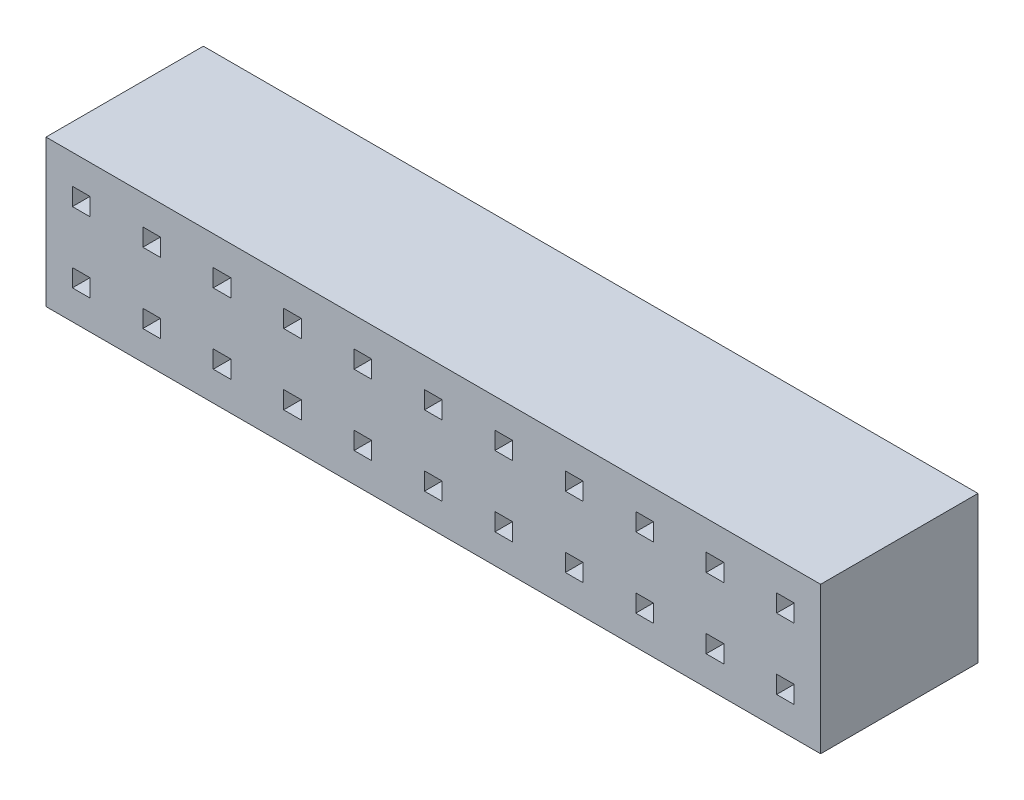
SolidWorks part; units mm, degrees
ref_plane "Front Plane" through (0, 0, 0) normal (0, 0, 1) x (1, 0, 0)
ref_plane "Top Plane" through (0, 0, 0) normal (0, 1, 0) x (1, 0, 0)
ref_plane "Right Plane" through (0, 0, 0) normal (1, 0, 0) x (0, 0, -1)
sketch "Sketch1" plane through (0, 0, 0) normal (0, 0, 1) x (1, 0, 0)
  line L1 (0, -0.085) -> (22, -0.085)
  line L2 (0, -0.085) -> (0, 4.085)
  line L3 (0, 4.085) -> (22, 4.085)
  line L4 (22, -0.085) -> (22, 4.085)
extrude "Boss-Extrude1" add sketch "Sketch1" along normal blind 4.47
sketch "Sketch2" plane through (0, 0, 4.47) normal (0, 0, 1) x (1, 0, 0)
  line L1 (0.75, 0.75) -> (1.25, 0.75)
  line L2 (0.75, 0.75) -> (0.75, 1.25)
  line L3 (0.75, 1.25) -> (1.25, 1.25)
  line L4 (1.25, 0.75) -> (1.25, 1.25)
  line L88 (2.75, 0.75) -> (3.25, 0.75)
  line L89 (2.75, 0.75) -> (2.75, 1.25)
  line L90 (2.75, 1.25) -> (3.25, 1.25)
  line L91 (3.25, 0.75) -> (3.25, 1.25)
  line L92 (4.75, 0.75) -> (5.25, 0.75)
  line L93 (4.75, 0.75) -> (4.75, 1.25)
  line L94 (4.75, 1.25) -> (5.25, 1.25)
  line L95 (5.25, 0.75) -> (5.25, 1.25)
  line L96 (6.75, 0.75) -> (7.25, 0.75)
  line L97 (6.75, 0.75) -> (6.75, 1.25)
  line L98 (6.75, 1.25) -> (7.25, 1.25)
  line L99 (7.25, 0.75) -> (7.25, 1.25)
  line L100 (8.75, 0.75) -> (9.25, 0.75)
  line L101 (8.75, 0.75) -> (8.75, 1.25)
  line L102 (8.75, 1.25) -> (9.25, 1.25)
  line L103 (9.25, 0.75) -> (9.25, 1.25)
  line L104 (10.75, 0.75) -> (11.25, 0.75)
  line L105 (10.75, 0.75) -> (10.75, 1.25)
  line L106 (10.75, 1.25) -> (11.25, 1.25)
  line L107 (11.25, 0.75) -> (11.25, 1.25)
  line L108 (12.75, 0.75) -> (13.25, 0.75)
  line L109 (12.75, 0.75) -> (12.75, 1.25)
  line L110 (12.75, 1.25) -> (13.25, 1.25)
  line L111 (13.25, 0.75) -> (13.25, 1.25)
  line L112 (14.75, 0.75) -> (15.25, 0.75)
  line L113 (14.75, 0.75) -> (14.75, 1.25)
  line L114 (14.75, 1.25) -> (15.25, 1.25)
  line L115 (15.25, 0.75) -> (15.25, 1.25)
  line L116 (16.75, 0.75) -> (17.25, 0.75)
  line L117 (16.75, 0.75) -> (16.75, 1.25)
  line L118 (16.75, 1.25) -> (17.25, 1.25)
  line L119 (17.25, 0.75) -> (17.25, 1.25)
  line L120 (18.75, 0.75) -> (19.25, 0.75)
  line L121 (18.75, 0.75) -> (18.75, 1.25)
  line L122 (18.75, 1.25) -> (19.25, 1.25)
  line L123 (19.25, 0.75) -> (19.25, 1.25)
  line L124 (20.75, 0.75) -> (21.25, 0.75)
  line L125 (20.75, 0.75) -> (20.75, 1.25)
  line L126 (20.75, 1.25) -> (21.25, 1.25)
  line L127 (21.25, 0.75) -> (21.25, 1.25)
  line L128 (0.75, 2.75) -> (1.25, 2.75)
  line L129 (0.75, 2.75) -> (0.75, 3.25)
  line L130 (0.75, 3.25) -> (1.25, 3.25)
  line L131 (1.25, 2.75) -> (1.25, 3.25)
  line L132 (2.75, 2.75) -> (3.25, 2.75)
  line L133 (2.75, 2.75) -> (2.75, 3.25)
  line L134 (2.75, 3.25) -> (3.25, 3.25)
  line L135 (3.25, 2.75) -> (3.25, 3.25)
  line L136 (4.75, 2.75) -> (5.25, 2.75)
  line L137 (4.75, 2.75) -> (4.75, 3.25)
  line L138 (4.75, 3.25) -> (5.25, 3.25)
  line L139 (5.25, 2.75) -> (5.25, 3.25)
  line L140 (6.75, 2.75) -> (7.25, 2.75)
  line L141 (6.75, 2.75) -> (6.75, 3.25)
  line L142 (6.75, 3.25) -> (7.25, 3.25)
  line L143 (7.25, 2.75) -> (7.25, 3.25)
  line L144 (8.75, 2.75) -> (9.25, 2.75)
  line L145 (8.75, 2.75) -> (8.75, 3.25)
  line L146 (8.75, 3.25) -> (9.25, 3.25)
  line L147 (9.25, 2.75) -> (9.25, 3.25)
  line L148 (10.75, 2.75) -> (11.25, 2.75)
  line L149 (10.75, 2.75) -> (10.75, 3.25)
  line L150 (10.75, 3.25) -> (11.25, 3.25)
  line L151 (11.25, 2.75) -> (11.25, 3.25)
  line L152 (12.75, 2.75) -> (13.25, 2.75)
  line L153 (12.75, 2.75) -> (12.75, 3.25)
  line L154 (12.75, 3.25) -> (13.25, 3.25)
  line L155 (13.25, 2.75) -> (13.25, 3.25)
  line L156 (14.75, 2.75) -> (15.25, 2.75)
  line L157 (14.75, 2.75) -> (14.75, 3.25)
  line L158 (14.75, 3.25) -> (15.25, 3.25)
  line L159 (15.25, 2.75) -> (15.25, 3.25)
  line L160 (16.75, 2.75) -> (17.25, 2.75)
  line L161 (16.75, 2.75) -> (16.75, 3.25)
  line L162 (16.75, 3.25) -> (17.25, 3.25)
  line L163 (17.25, 2.75) -> (17.25, 3.25)
  line L164 (18.75, 2.75) -> (19.25, 2.75)
  line L165 (18.75, 2.75) -> (18.75, 3.25)
  line L166 (18.75, 3.25) -> (19.25, 3.25)
  line L167 (19.25, 2.75) -> (19.25, 3.25)
  line L168 (20.75, 2.75) -> (21.25, 2.75)
  line L169 (20.75, 2.75) -> (20.75, 3.25)
  line L170 (20.75, 3.25) -> (21.25, 3.25)
  line L171 (21.25, 2.75) -> (21.25, 3.25)
  dimension "D2" = 2
  dimension "D1" = 11
extrude "Cut-Extrude1" cut sketch "Sketch2" against normal blind 4.47
